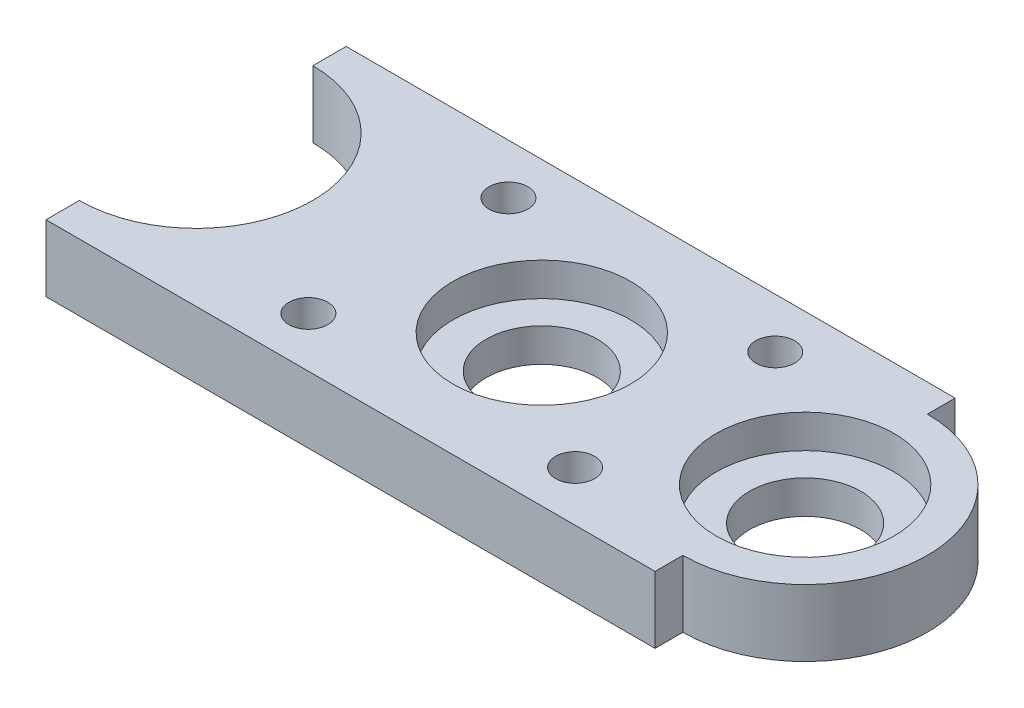
SolidWorks part; units mm, degrees
ref_plane "Front Plane" through (0, 0, 0) normal (0, 0, 1) x (1, 0, 0)
ref_plane "Top Plane" through (0, 0, 0) normal (0, 1, 0) x (1, 0, 0)
ref_plane "Right Plane" through (0, 0, 0) normal (1, 0, 0) x (0, 0, -1)
sketch "Sketch1" plane through (0, 0, 0) normal (0, 1, 0) x (1, 0, 0)
  line L1 (-31.1, 13.5) -> (23.69, 13.5)
  line L2 (-31.1, 13.5) -> (-31.1, -13.5)
  line L3 (-31.1, -13.5) -> (23.69, -13.5)
  line L4 (23.69, 13.5) -> (23.69, -13.5)
  circle A0 centre (23.69, 0) radius 11
  circle A1 centre (-31.1, 0) radius 10.5
  circle A2 centre (12, 9) radius 1.75
  circle A3 centre (23.69, 0) radius 5
  circle A4 centre (0, 0) radius 5
  circle A5 centre (12, -9) radius 1.75
  circle A6 centre (-12, -9) radius 1.75
  circle A7 centre (-12, 9) radius 1.75
  dimension "D5" = 22
  dimension "D6" = 21
  dimension "D7" = 3.5
  dimension "D10" = 10
  dimension "D11" = 10
  dimension "D12" = 3.5
  dimension "D15" = 3.5
  dimension "D17" = 3.5
  dimension "D1" = 31.1
  dimension "D2" = 23.69
  dimension "D3" = 27
  dimension "D4" = 13.5
  dimension "D8" = 12
  dimension "D9" = 9
  dimension "D13" = 12
  dimension "D14" = 9
  dimension "D16" = 12
extrude "Boss-Extrude1" add sketch "Sketch1" along normal blind 6 contours A1 L2 L3 L4 A0 L1 A7 A6 A5 A4 A2 | A3 L4 A0 | A3 L4 A0
sketch "Sketch2" plane through (0, 0, 0) normal (0, -1, 0) x (1, 0, 0)
  circle A0 centre (12, -9) radius 1.75 construction
  circle A1 centre (12, 9) radius 1.75 construction
  circle A2 centre (-12, 9) radius 1.75 construction
  circle A3 centre (-12, -9) radius 1.75 construction
  circle A4 centre (12, -9) radius 1.75
  circle A5 centre (12, 9) radius 1.75
  circle A6 centre (-12, 9) radius 1.75
  circle A7 centre (-12, -9) radius 1.75
  circle A8 centre (-12, -9) radius 3
  circle A9 centre (-12, 9) radius 3
  circle A10 centre (12, 9) radius 3
  circle A11 centre (12, -9) radius 3
  dimension "D1" = 6
  dimension "D2" = 6
  dimension "D3" = 6
  dimension "D4" = 6
extrude "Cut-Extrude1" cut sketch "Sketch2" against normal blind 3
sketch "Sketch3" plane through (0, 6, 0) normal (0, 1, 0) x (1, 0, 0)
  circle A0 centre (0, 0) radius 8
  circle A1 centre (0, 0) radius 5 construction
  circle A2 centre (23.69, 0) radius 5 construction
  circle A3 centre (0, 0) radius 5
  circle A4 centre (23.69, 0) radius 5
  circle A5 centre (23.69, 0) radius 8
  dimension "D1" = 16
  dimension "D2" = 16
extrude "Cut-Extrude2" cut sketch "Sketch3" against normal blind 3
